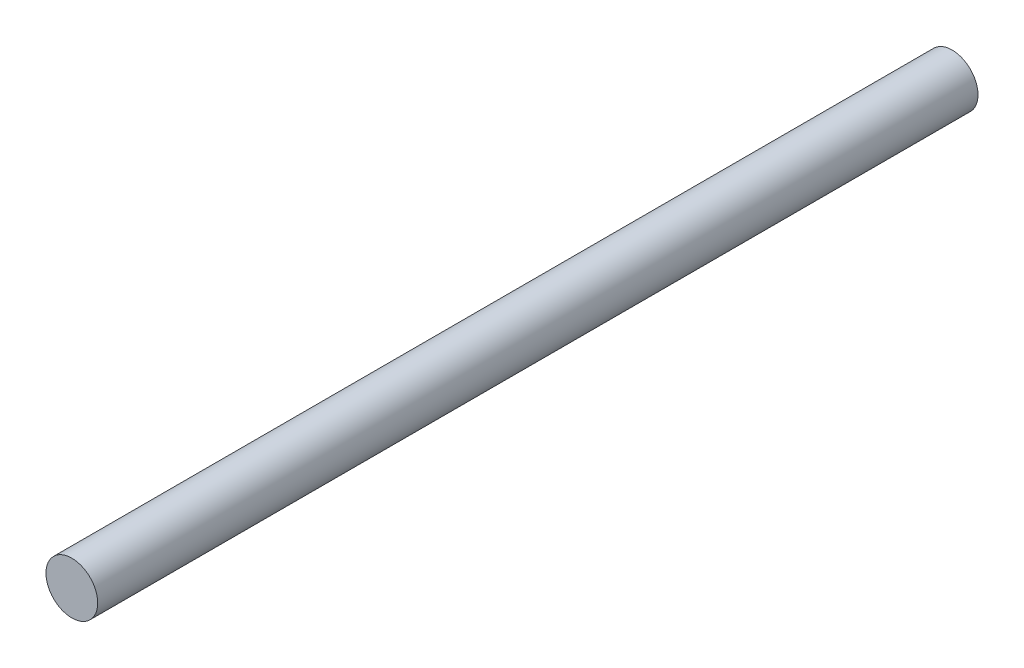
SolidWorks part; units mm, degrees
ref_plane "Front" through (0, 0, 0) normal (0, 0, 1) x (1, 0, 0)
ref_plane "Top" through (0, 0, 0) normal (0, 1, 0) x (1, 0, 0)
ref_plane "Right" through (0, 0, 0) normal (1, 0, 0) x (0, 0, -1)
sketch "Sketch1" plane through (0, 0, 0) normal (0, 0, 1) x (1, 0, 0)
  circle A0 centre (0, 0) radius 1.5875
  dimension "D1" = 3.175
extrude "Boss-Extrude1" add sketch "Sketch1" along normal blind 53.975
